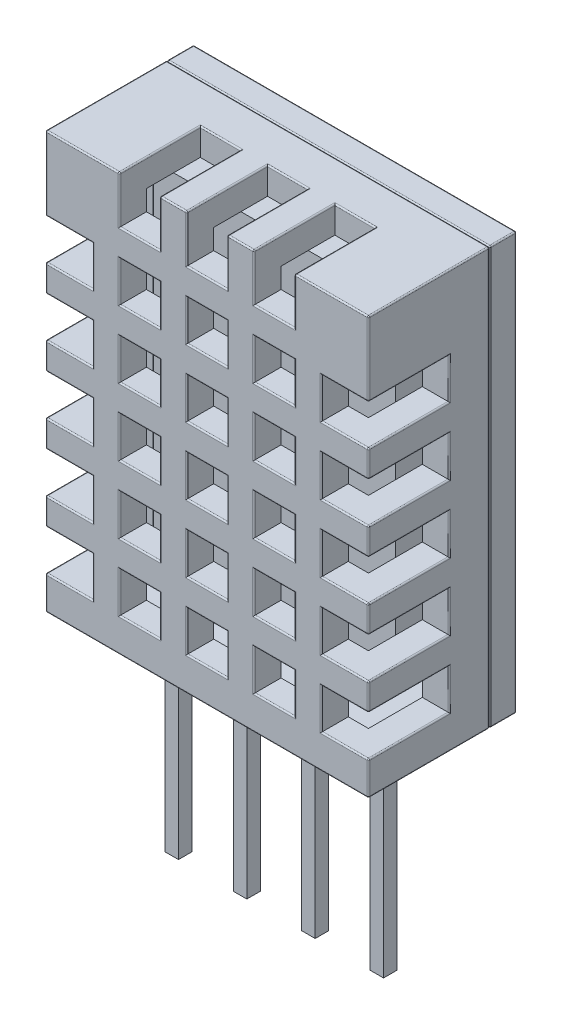
SolidWorks part; units mm, degrees
ref_plane "Front Plane" through (0, 0, 0) normal (0, 0, 1) x (1, 0, 0)
ref_plane "Top Plane" through (0, 0, 0) normal (0, 1, 0) x (1, 0, 0)
ref_plane "Right Plane" through (0, 0, 0) normal (1, 0, 0) x (0, 0, -1)
sketch "Sketch1" plane through (0, 0, 0) normal (0, 0, 1) x (1, 0, 0)
  line L1 (0, 0) -> (12, 0)
  line L2 (0, 0) -> (0, 15.5)
  line L3 (0, 15.5) -> (12, 15.5)
  line L4 (12, 0) -> (12, 15.5)
  dimension "D1" = 12
  dimension "D2" = 15.5
extrude "Boss-Extrude1" add sketch "Sketch1" along normal blind 5.5
sketch "Sketch2" plane through (0, 0, 0) normal (0, -1, 0) x (1, 0, 0)
  line L0 (0, 5.5) -> (0, 0) construction
  line L1 (1.94, 3) -> (2.44, 3)
  line L2 (1.94, 3) -> (1.94, 2.5)
  line L3 (1.94, 2.5) -> (2.44, 2.5)
  line L4 (2.44, 3) -> (2.44, 2.5)
  line L5 (0, 2.75) -> (12, 2.75) construction
  line L6 (12, 5.5) -> (12, 0) construction
  line L7 (4.48, 3) -> (4.98, 3)
  line L8 (4.48, 3) -> (4.48, 2.5)
  line L9 (4.48, 2.5) -> (4.98, 2.5)
  line L10 (4.98, 3) -> (4.98, 2.5)
  line L11 (7.02, 3) -> (7.52, 3)
  line L12 (7.02, 3) -> (7.02, 2.5)
  line L13 (7.02, 2.5) -> (7.52, 2.5)
  line L14 (7.52, 3) -> (7.52, 2.5)
  line L15 (9.56, 3) -> (10.06, 3)
  line L16 (9.56, 3) -> (9.56, 2.5)
  line L17 (9.56, 2.5) -> (10.06, 2.5)
  line L18 (10.06, 3) -> (10.06, 2.5)
  point P11 (1.94, 2.75)
  dimension "D1" = 0.5
  dimension "D2" = 0.5
  dimension "D3" = 1.94
  dimension "D4" = 4
extrude "Boss-Extrude2" add sketch "Sketch2" along normal blind 8
shell "Shell2" thickness 1
sketch "Sketch3" plane through (0, 0, 5.5) normal (0, 0, 1) x (1, 0, 0)
  line L0 (12, 15.5) -> (0, 15.5) construction
  line L1 (2.75, 15.5) -> (4.25, 15.5)
  line L2 (2.75, 15.5) -> (2.75, 13.75)
  line L3 (2.75, 13.75) -> (4.25, 13.75)
  line L4 (4.25, 15.5) -> (4.25, 13.75)
  line L5 (5.25, 15.5) -> (6.75, 15.5)
  line L6 (5.25, 15.5) -> (5.25, 13.75)
  line L7 (5.25, 13.75) -> (6.75, 13.75)
  line L8 (6.75, 15.5) -> (6.75, 13.75)
  line L9 (7.75, 15.5) -> (9.25, 15.5)
  line L10 (7.75, 15.5) -> (7.75, 13.75)
  line L11 (7.75, 13.75) -> (9.25, 13.75)
  line L12 (9.25, 15.5) -> (9.25, 13.75)
  line L13 (0, 15.5) -> (0, 0) construction
  dimension "D1" = 1.5
  dimension "D2" = 1.75
  dimension "D4" = 2.75
  dimension "D3" = 3
extrude "Cut-Extrude1" cut sketch "Sketch3" against normal blind 3
sketch "Sketch4" plane through (0, 0, 5.5) normal (0, 0, 1) x (1, 0, 0)
  line L0 (2.75, 13.75) -> (4.25, 13.75) construction
  line L1 (2.75, 12.75) -> (4.25, 12.75)
  line L2 (2.75, 12.75) -> (2.75, 11.25)
  line L3 (2.75, 11.25) -> (4.25, 11.25)
  line L4 (4.25, 12.75) -> (4.25, 11.25)
  line L5 (0, 15.5) -> (0, 0) construction
  line L6 (5.25, 12.75) -> (6.75, 12.75)
  line L7 (5.25, 12.75) -> (5.25, 11.25)
  line L8 (5.25, 11.25) -> (6.75, 11.25)
  line L9 (6.75, 12.75) -> (6.75, 11.25)
  line L10 (7.75, 12.75) -> (9.25, 12.75)
  line L11 (7.75, 12.75) -> (7.75, 11.25)
  line L12 (7.75, 11.25) -> (9.25, 11.25)
  line L13 (9.25, 12.75) -> (9.25, 11.25)
  line L14 (5.25, 10.25) -> (6.75, 10.25)
  line L15 (5.25, 10.25) -> (5.25, 8.75)
  line L16 (5.25, 8.75) -> (6.75, 8.75)
  line L17 (6.75, 10.25) -> (6.75, 8.75)
  line L18 (7.75, 10.25) -> (9.25, 10.25)
  line L19 (7.75, 10.25) -> (7.75, 8.75)
  line L20 (7.75, 8.75) -> (9.25, 8.75)
  line L21 (9.25, 10.25) -> (9.25, 8.75)
  line L22 (5.25, 7.75) -> (6.75, 7.75)
  line L23 (5.25, 7.75) -> (5.25, 6.25)
  line L24 (5.25, 6.25) -> (6.75, 6.25)
  line L25 (6.75, 7.75) -> (6.75, 6.25)
  line L26 (7.75, 7.75) -> (9.25, 7.75)
  line L27 (7.75, 7.75) -> (7.75, 6.25)
  line L28 (7.75, 6.25) -> (9.25, 6.25)
  line L29 (9.25, 7.75) -> (9.25, 6.25)
  line L30 (5.25, 5.25) -> (6.75, 5.25)
  line L31 (5.25, 5.25) -> (5.25, 3.75)
  line L32 (5.25, 3.75) -> (6.75, 3.75)
  line L33 (6.75, 5.25) -> (6.75, 3.75)
  line L34 (7.75, 5.25) -> (9.25, 5.25)
  line L35 (7.75, 5.25) -> (7.75, 3.75)
  line L36 (7.75, 3.75) -> (9.25, 3.75)
  line L37 (9.25, 5.25) -> (9.25, 3.75)
  line L38 (5.25, 2.75) -> (6.75, 2.75)
  line L39 (5.25, 2.75) -> (5.25, 1.25)
  line L40 (5.25, 1.25) -> (6.75, 1.25)
  line L41 (6.75, 2.75) -> (6.75, 1.25)
  line L42 (7.75, 2.75) -> (9.25, 2.75)
  line L43 (7.75, 2.75) -> (7.75, 1.25)
  line L44 (7.75, 1.25) -> (9.25, 1.25)
  line L45 (9.25, 2.75) -> (9.25, 1.25)
  line L46 (2.75, 10.25) -> (4.25, 10.25)
  line L47 (2.75, 10.25) -> (2.75, 8.75)
  line L48 (2.75, 8.75) -> (4.25, 8.75)
  line L49 (4.25, 10.25) -> (4.25, 8.75)
  line L50 (2.75, 7.75) -> (4.25, 7.75)
  line L51 (2.75, 7.75) -> (2.75, 6.25)
  line L52 (2.75, 6.25) -> (4.25, 6.25)
  line L53 (4.25, 7.75) -> (4.25, 6.25)
  line L54 (2.75, 5.25) -> (4.25, 5.25)
  line L55 (2.75, 5.25) -> (2.75, 3.75)
  line L56 (2.75, 3.75) -> (4.25, 3.75)
  line L57 (4.25, 5.25) -> (4.25, 3.75)
  line L58 (2.75, 2.75) -> (4.25, 2.75)
  line L59 (2.75, 2.75) -> (2.75, 1.25)
  line L60 (2.75, 1.25) -> (4.25, 1.25)
  line L61 (4.25, 2.75) -> (4.25, 1.25)
  dimension "D1" = 1.5
  dimension "D2" = 1
  dimension "D3" = 2.75
  dimension "D4" = 3
  dimension "D5" = 5
extrude "Cut-Extrude2" cut sketch "Sketch4" against normal blind 3
sketch "Sketch5" plane through (0, 0, 5.5) normal (0, 0, 1) x (1, 0, 0)
  line L0 (0, 15.5) -> (0, 0) construction
  line L1 (0, 12.75) -> (1.75, 12.75)
  line L2 (0, 12.75) -> (0, 11.25)
  line L3 (0, 11.25) -> (1.75, 11.25)
  line L4 (1.75, 12.75) -> (1.75, 11.25)
  line L7 (2.75, 12.75) -> (2.75, 11.25) construction
  line L8 (10.25, 12.75) -> (12, 12.75)
  line L9 (10.25, 12.75) -> (10.25, 11.25)
  line L10 (10.25, 11.25) -> (12, 11.25)
  line L11 (12, 12.75) -> (12, 11.25)
  line L12 (10.25, 10.25) -> (12, 10.25)
  line L13 (10.25, 10.25) -> (10.25, 8.75)
  line L14 (10.25, 8.75) -> (12, 8.75)
  line L15 (12, 10.25) -> (12, 8.75)
  line L16 (10.25, 7.75) -> (12, 7.75)
  line L17 (10.25, 7.75) -> (10.25, 6.25)
  line L18 (10.25, 6.25) -> (12, 6.25)
  line L19 (12, 7.75) -> (12, 6.25)
  line L20 (10.25, 5.25) -> (12, 5.25)
  line L21 (10.25, 5.25) -> (10.25, 3.75)
  line L22 (10.25, 3.75) -> (12, 3.75)
  line L23 (12, 5.25) -> (12, 3.75)
  line L24 (10.25, 2.75) -> (12, 2.75)
  line L25 (10.25, 2.75) -> (10.25, 1.25)
  line L26 (10.25, 1.25) -> (12, 1.25)
  line L27 (12, 2.75) -> (12, 1.25)
  line L28 (0, 10.25) -> (1.75, 10.25)
  line L29 (0, 10.25) -> (0, 8.75)
  line L30 (0, 8.75) -> (1.75, 8.75)
  line L31 (1.75, 10.25) -> (1.75, 8.75)
  line L32 (0, 7.75) -> (1.75, 7.75)
  line L33 (0, 7.75) -> (0, 6.25)
  line L34 (0, 6.25) -> (1.75, 6.25)
  line L35 (1.75, 7.75) -> (1.75, 6.25)
  line L36 (0, 5.25) -> (1.75, 5.25)
  line L37 (0, 5.25) -> (0, 3.75)
  line L38 (0, 3.75) -> (1.75, 3.75)
  line L39 (1.75, 5.25) -> (1.75, 3.75)
  line L40 (0, 2.75) -> (1.75, 2.75)
  line L41 (0, 2.75) -> (0, 1.25)
  line L42 (0, 1.25) -> (1.75, 1.25)
  line L43 (1.75, 2.75) -> (1.75, 1.25)
  dimension "D1" = 1
  dimension "D2" = 2
  dimension "D3" = 5
extrude "Cut-Extrude3" cut sketch "Sketch5" against normal blind 3
sketch "Sketch6" plane through (0, 0, 0) normal (0, 0, -1) x (-1, 0, 0)
  line L4 (0, 0) -> (0, 15.5)
  line L5 (0, 15.5) -> (-12, 15.5)
  line L6 (-12, 15.5) -> (-12, 0)
  line L7 (-12, 0) -> (0, 0)
  line L8 (0, 0) -> (0, 15.5)
  line L9 (0, 15.5) -> (-12, 15.5)
  line L10 (-12, 15.5) -> (-12, 0)
  line L11 (-12, 0) -> (0, 0)
  line L12 (-1, 14.5) -> (-11, 14.5)
  line L13 (-1, 1) -> (-1, 14.5)
  line L14 (-11, 1) -> (-1, 1)
  line L15 (-11, 14.5) -> (-11, 1)
  line L16 (-1, 14.5) -> (-11, 14.5)
  line L17 (-1, 1) -> (-1, 14.5)
  line L18 (-11, 1) -> (-1, 1)
  line L19 (-11, 14.5) -> (-11, 1)
  dimension "D1" = 0
  dimension "D2" = 0
extrude "Cut-Extrude4" cut sketch "Sketch6" against normal blind 1
ref_plane "Plane1" through (0, 0, 0.99) normal (0, 0, 1) x (1, 0, 0)
sketch "Sketch8" plane through (0, 0, 0.99) normal (0, 0, 1) x (1, 0, 0)
  line L4 (0, 0) -> (12, 0)
  line L5 (0, 15.5) -> (0, 0)
  line L6 (12, 15.5) -> (0, 15.5)
  line L7 (12, 0) -> (12, 15.5)
  line L8 (0, 0) -> (12, 0)
  line L9 (0, 15.5) -> (0, 0)
  line L10 (12, 15.5) -> (0, 15.5)
  line L11 (12, 0) -> (12, 15.5)
  dimension "D1" = 0
extrude "Boss-Extrude3" add sketch "Sketch8" against normal blind 0.99 separate body
sketch "Sketch9" plane through (0, 0, 0) normal (0, -1, 0) x (1, 0, 0)
  line L0 (1.94, 3) -> (1.94, 2.5) construction
  line L1 (1.94, 2.5) -> (2.44, 2.5) construction
  line L2 (2.44, 2.5) -> (2.44, 3) construction
  line L3 (2.44, 3) -> (1.94, 3) construction
  line L4 (4.48, 3) -> (4.48, 2.5) construction
  line L5 (4.48, 2.5) -> (4.98, 2.5) construction
  line L6 (4.98, 2.5) -> (4.98, 3) construction
  line L7 (4.98, 3) -> (4.48, 3) construction
  line L8 (7.02, 3) -> (7.02, 2.5) construction
  line L9 (7.02, 2.5) -> (7.52, 2.5) construction
  line L10 (7.52, 2.5) -> (7.52, 3) construction
  line L11 (7.52, 3) -> (7.02, 3) construction
  line L12 (9.56, 3) -> (9.56, 2.5) construction
  line L13 (9.56, 2.5) -> (10.06, 2.5) construction
  line L14 (10.06, 2.5) -> (10.06, 3) construction
  line L15 (10.06, 3) -> (9.56, 3) construction
  line L16 (1.94, 3) -> (1.94, 2.5)
  line L17 (1.94, 2.5) -> (2.44, 2.5)
  line L18 (2.44, 2.5) -> (2.44, 3)
  line L19 (2.44, 3) -> (1.94, 3)
  line L20 (4.48, 3) -> (4.48, 2.5)
  line L21 (4.48, 2.5) -> (4.98, 2.5)
  line L22 (4.98, 2.5) -> (4.98, 3)
  line L23 (4.98, 3) -> (4.48, 3)
  line L24 (7.02, 3) -> (7.02, 2.5)
  line L25 (7.02, 2.5) -> (7.52, 2.5)
  line L26 (7.52, 2.5) -> (7.52, 3)
  line L27 (7.52, 3) -> (7.02, 3)
  line L28 (9.56, 3) -> (9.56, 2.5)
  line L29 (9.56, 2.5) -> (10.06, 2.5)
  line L30 (10.06, 2.5) -> (10.06, 3)
  line L31 (10.06, 3) -> (9.56, 3)
  line L32 (1.84, 3.1) -> (1.84, 2.4)
  line L33 (1.84, 2.4) -> (2.54, 2.4)
  line L34 (2.54, 2.4) -> (2.54, 3.1)
  line L35 (2.54, 3.1) -> (1.84, 3.1)
  line L36 (4.38, 3.1) -> (4.38, 2.4)
  line L37 (4.38, 2.4) -> (5.08, 2.4)
  line L38 (5.08, 2.4) -> (5.08, 3.1)
  line L39 (5.08, 3.1) -> (4.38, 3.1)
  line L40 (6.92, 3.1) -> (6.92, 2.4)
  line L41 (6.92, 2.4) -> (7.62, 2.4)
  line L42 (7.62, 2.4) -> (7.62, 3.1)
  line L43 (7.62, 3.1) -> (6.92, 3.1)
  line L44 (9.46, 3.1) -> (9.46, 2.4)
  line L45 (9.46, 2.4) -> (10.16, 2.4)
  line L46 (10.16, 2.4) -> (10.16, 3.1)
  line L47 (10.16, 3.1) -> (9.46, 3.1)
  dimension "D1" = 0.1
extrude "Cut-Extrude5" cut sketch "Sketch9" against normal blind 1
fillet "Fillet1" radius 0.05 106 edges at (6, 0, 1) (2.54, 0, 2.75) (1.84, 0, 2.75) (4.73, 0, 2.4) (4.73, 0, 3.1) (7.27, 0, 2.4) (7.27, 0, 3.1) (9.81, 0, 2.4) (9.81, 0, 3.1) (9.46, 0, 2.75) (0, 12, 2.5) (0, 11.25, 4) (0, 9.5, 2.5) (0, 8.75, 4) (0, 7, 2.5) (0, 6.25, 4) (0, 5.25, 4) (0, 4.5, 2.5) (0, 3.75, 4) (0, 2.75, 4) (0, 2, 2.5) (0, 1.25, 4) (9.25, 15.5, 4) (8.5, 15.5, 2.5) (7.75, 15.5, 4) (6.75, 15.5, 4) (4.25, 15.5, 4) (3.5, 15.5, 2.5) (6, 15.5, 1) (12, 0, 3.25) (12, 1.25, 4) (12, 2.75, 4) (12, 3.75, 4) (12, 4.5, 2.5) (12, 6.25, 4) (12, 7, 2.5) (12, 7.75, 4) (12, 8.75, 4) (12, 10.25, 4) (12, 12, 2.5) (12, 12.75, 4) (12, 15.5, 3.25) (12, 7.75, 1) (0.875, 5.25, 5.5) (0, 5.75, 5.5) (1.75, 7, 5.5) (0.875, 7.75, 5.5) (0, 8.25, 5.5) (0.875, 8.75, 5.5) (0, 10.75, 5.5) (1.75, 12, 5.5) (0.875, 12.75, 5.5) (0, 14.125, 5.5) (1.375, 15.5, 5.5) (2.75, 14.625, 5.5) (3.5, 13.75, 5.5) (4.25, 14.625, 5.5) (4.75, 15.5, 5.5) (7.75, 14.625, 5.5) (8.5, 13.75, 5.5) (9.25, 14.625, 5.5) (11.125, 12.75, 5.5) (10.25, 12, 5.5) (12, 10.75, 5.5) (10.25, 9.5, 5.5) (12, 8.25, 5.5) (10.25, 7, 5.5) (11.125, 6.25, 5.5) (11.125, 3.75, 5.5) (12, 3.25, 5.5) (11.125, 2.75, 5.5) (12, 0.625, 5.5) (6, 0, 5.5) (0.875, 1.25, 5.5) (1.75, 2, 5.5) (0.875, 2.75, 5.5) (0, 3.25, 5.5) (4.25, 12, 5.5) (3.5, 12.75, 5.5) (6.75, 12, 5.5) (6, 12.75, 5.5) (5.25, 12, 5.5) (9.25, 12, 5.5) (6, 10.25, 5.5) (6, 8.75, 5.5) (9.25, 9.5, 5.5) (9.25, 7, 5.5) (8.5, 7.75, 5.5) (7.75, 7, 5.5) (5.25, 4.5, 5.5) (9.25, 4.5, 5.5) (8.5, 5.25, 5.5) (8.5, 3.75, 5.5) (6.75, 2, 5.5) (9.25, 2, 5.5) (8.5, 2.75, 5.5) (4.25, 9.5, 5.5) (3.5, 8.75, 5.5) (4.25, 7, 5.5) (3.5, 7.75, 5.5) (2.75, 7, 5.5) (4.25, 4.5, 5.5) (3.5, 5.25, 5.5) (3.5, 2.75, 5.5) (2.75, 2, 5.5) (3.5, 1.25, 5.5)
fillet "Fillet2" radius 0.05 12 edges at (6, 15.5, 0.99) (0, 15.5, 0.495) (0, 7.75, 0.99) (0, 0, 0.495) (6, 0, 0.99) (12, 15.5, 0.495) (12, 0, 0.495) (12, 7.75, 0.99) (6, 15.5, 0) (0, 7.75, 0) (6, 0, 0) (12, 7.75, 0)
sketch "Sketch10" plane through (0, 0, 0.99) normal (0, 0, 1) x (1, 0, 0)
  line L14 (1.5, 1.5) -> (10.5, 1.5)
  line L15 (10.5, 1.5) -> (10.5, 14)
  line L16 (10.5, 14) -> (1.5, 14)
  line L17 (1.5, 14) -> (1.5, 1.5)
  line L18 (1.5, 1.5) -> (10.5, 1.5)
  line L19 (10.5, 1.5) -> (10.5, 14)
  line L20 (10.5, 14) -> (1.5, 14)
  line L21 (1.5, 14) -> (1.5, 1.5)
  dimension "D1" = 0.5
extrude "Boss-Extrude4" add sketch "Sketch10" along normal blind 2
